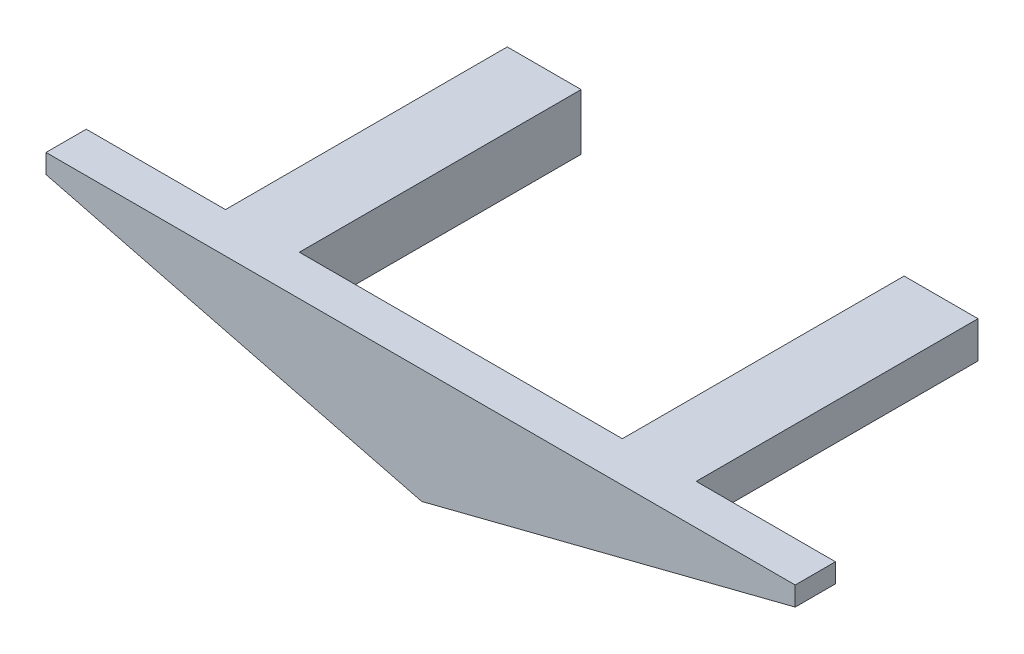
SolidWorks part; units mm, degrees
ref_plane "Front Plane" through (0, 0, 0) normal (0, 0, 1) x (1, 0, 0)
ref_plane "Top Plane" through (0, 0, 0) normal (0, 1, 0) x (1, 0, 0)
ref_plane "Right Plane" through (0, 0, 0) normal (1, 0, 0) x (0, 0, -1)
ref_plane "MOTOR_HOLDER_PLANE" through (0, 0, -35) normal (0, 0, 1) x (1, 0, 0)
sketch "Sketch2" plane through (0, 0, -35) normal (0, 0, 1) x (1, 0, 0)
  line L0 (-29.2357, -93.6191) -> (-29.2357, -98.1702)
  line L1 (-46.53, -93.6191) -> (-17.367, -93.6191) construction
  line L2 (-76, -85.8638) -> (-18.0693, -101.1087) construction
  line L3 (-29.2357, -98.1702) -> (-20.0598, -100.5849)
  line L4 (-20.0598, -100.5849) -> (-20.0598, -93.6191)
  line L5 (-20.0598, -93.6191) -> (-29.2357, -93.6191)
  line L6 (0, -55) -> (0, 55) construction
  line L7 (29.2357, -98.1702) -> (20.0598, -100.5849)
  line L8 (20.0598, -100.5849) -> (20.0598, -93.6191)
  line L9 (20.0598, -93.6191) -> (29.2357, -93.6191)
  line L10 (29.2357, -93.6191) -> (29.2357, -98.1702)
extrude "Boss-Extrude1" add sketch "Sketch2" along normal blind 40 separate body
sketch "Sketch3" plane through (0, 0, 0) normal (0, 0, 1) x (1, 0, 0)
  line L0 (-46.53, -93.6191) -> (0.133, -93.6191)
  line L1 (3.6737, -93.6191) -> (-3.4077, -93.6191) construction
  line L4 (-46.53, -95.9994) -> (-46.53, -93.6191)
  line L5 (0, -3.8312) -> (0, 3.8312) construction
  line L6 (46.53, -93.6191) -> (0.133, -93.6191)
  line L7 (46.53, -95.9994) -> (46.53, -93.6191)
  line L8 (46.53, -95.9994) -> (0.133, -107.8326)
  line L9 (0.133, -107.8326) -> (-46.53, -95.9994)
extrude "Boss-Extrude2" add sketch "Sketch3" along normal blind 5 separate body
